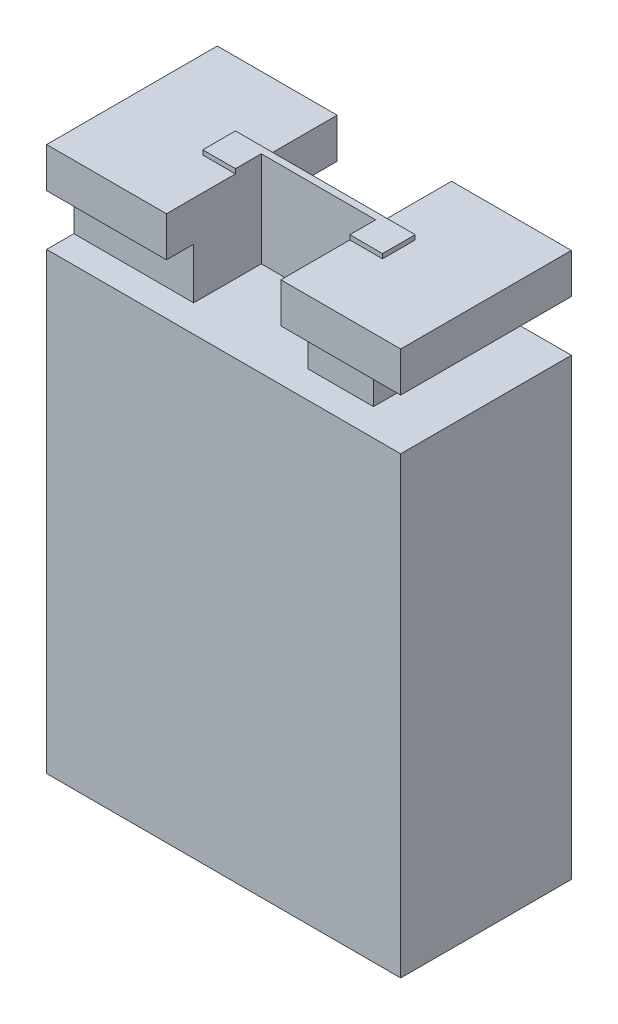
SolidWorks part; units mm, degrees
ref_plane "Front Plane" through (0, 0, 0) normal (0, 0, 1) x (1, 0, 0)
ref_plane "Top Plane" through (0, 0, 0) normal (0, 1, 0) x (1, 0, 0)
ref_plane "Right Plane" through (0, 0, 0) normal (1, 0, 0) x (0, 0, -1)
sketch "Sketch2" plane through (0, 0, 0) normal (0, 1, 0) x (1, 0, 0)
  line L1 (-2.4765, -1.1938) -> (2.4765, -1.1938)
  line L2 (-2.4765, -1.1938) -> (-2.4765, 1.1938)
  line L3 (-2.4765, 1.1938) -> (2.4765, 1.1938)
  line L4 (2.4765, -1.1938) -> (2.4765, 1.1938)
  line L5 (-2.4765, -1.1938) -> (2.4765, 1.1938) construction
  line L6 (-2.4765, 1.1938) -> (2.4765, -1.1938) construction
  point P0 (0, 0)
  dimension "D1" = 2.3876
  dimension "D2" = 4.953
extrude "Boss-Extrude1" add sketch "Sketch2" along normal blind 7.62
sketch "Sketch3" plane through (2.4765, 0, 0) normal (1, 0, 0) x (0, 0, -1)
  line L0 (-1.1938, 7.62) -> (-1.1938, 0) construction
  line L1 (-1.1938, 7.0612) -> (-0.8128, 7.0612)
  line L2 (-1.1938, 7.0612) -> (-1.1938, 6.35)
  line L3 (-1.1938, 6.35) -> (-0.8128, 6.35)
  line L4 (-0.8128, 7.0612) -> (-0.8128, 6.35)
  line L5 (1.1938, 7.62) -> (1.1938, 0) construction
  line L6 (1.1938, 7.0612) -> (0.8128, 7.0612)
  line L7 (1.1938, 7.0612) -> (1.1938, 6.35)
  line L8 (1.1938, 6.35) -> (0.8128, 6.35)
  line L9 (0.8128, 7.0612) -> (0.8128, 6.35)
  line L10 (-1.1938, 7.62) -> (1.1938, 7.62) construction
  dimension "D1" = 1.27
  dimension "D2" = 0.7112
  dimension "D3" = 0.381
extrude "Cut-Extrude1" cut sketch "Sketch3" against normal through all
sketch "Sketch4" plane through (0, 0, 0.8128) normal (0, 0, 1) x (1, 0, 0)
  line L0 (-2.4765, 7.0612) -> (2.4765, 7.0612) construction
  line L1 (2.4765, 6.35) -> (1.7145, 6.35)
  line L2 (2.4765, 6.35) -> (2.4765, 7.0612)
  line L3 (2.4765, 7.0612) -> (1.7145, 7.0612)
  line L4 (1.7145, 6.35) -> (1.7145, 7.0612)
  dimension "D1" = 0.762
extrude "Cut-Extrude2" cut sketch "Sketch4" against normal up to next
sketch "Sketch5" plane through (0, 7.62, 0) normal (0, 1, 0) x (1, 0, 0)
  line L0 (2.4765, 1.1938) -> (-2.4765, 1.1938) construction
  line L1 (-0.8001, -1.1938) -> (0.8001, -1.1938)
  line L2 (-0.8001, -1.1938) -> (-0.8001, 0.1323)
  line L3 (-0.8001, 0.1323) -> (0.8001, 0.1323)
  line L4 (0.8001, -1.1938) -> (0.8001, 0.1323)
  line L5 (-0.8001, 0.2286) -> (0.8001, 0.2286)
  line L6 (-0.8001, 0.2286) -> (-0.8001, 1.1938)
  line L7 (-0.8001, 1.1938) -> (0.8001, 1.1938)
  line L8 (0.8001, 0.2286) -> (0.8001, 1.1938)
  line L9 (-2.4765, -1.1938) -> (2.4765, -1.1938) construction
  point P8 (0, 1.1938)
  dimension "D1" = 0.0963
  dimension "D2" = 1.6002
  dimension "D3" = 0.9652
extrude "Cut-Extrude3" cut sketch "Sketch5" against normal up to surface (1.27 mm away)
sketch "Sketch6" plane through (0, 7.62, 0) normal (0, 1, 0) x (1, 0, 0)
  line L0 (-0.8001, 0.1323) -> (0.8001, 0.1323)
  line L1 (-0.8001, 0.2286) -> (-1.2573, 0.2286)
  line L2 (-0.8001, 0.1323) -> (-0.8001, -0.2286)
  line L3 (-0.8001, -0.2286) -> (-1.2573, -0.2286)
  line L4 (-1.2573, 0.2286) -> (-1.2573, -0.2286)
  line L5 (0.8001, 0.2286) -> (1.2573, 0.2286)
  line L6 (0.8001, 0.1323) -> (0.8001, -0.2286)
  line L7 (0.8001, -0.2286) -> (1.2573, -0.2286)
  line L8 (1.2573, 0.2286) -> (1.2573, -0.2286)
  line L9 (0.8001, 0.2286) -> (-0.8001, 0.2286)
  dimension "D1" = 0.4572
extrude "Boss-Extrude2" add sketch "Sketch6" along normal blind 0.0635
